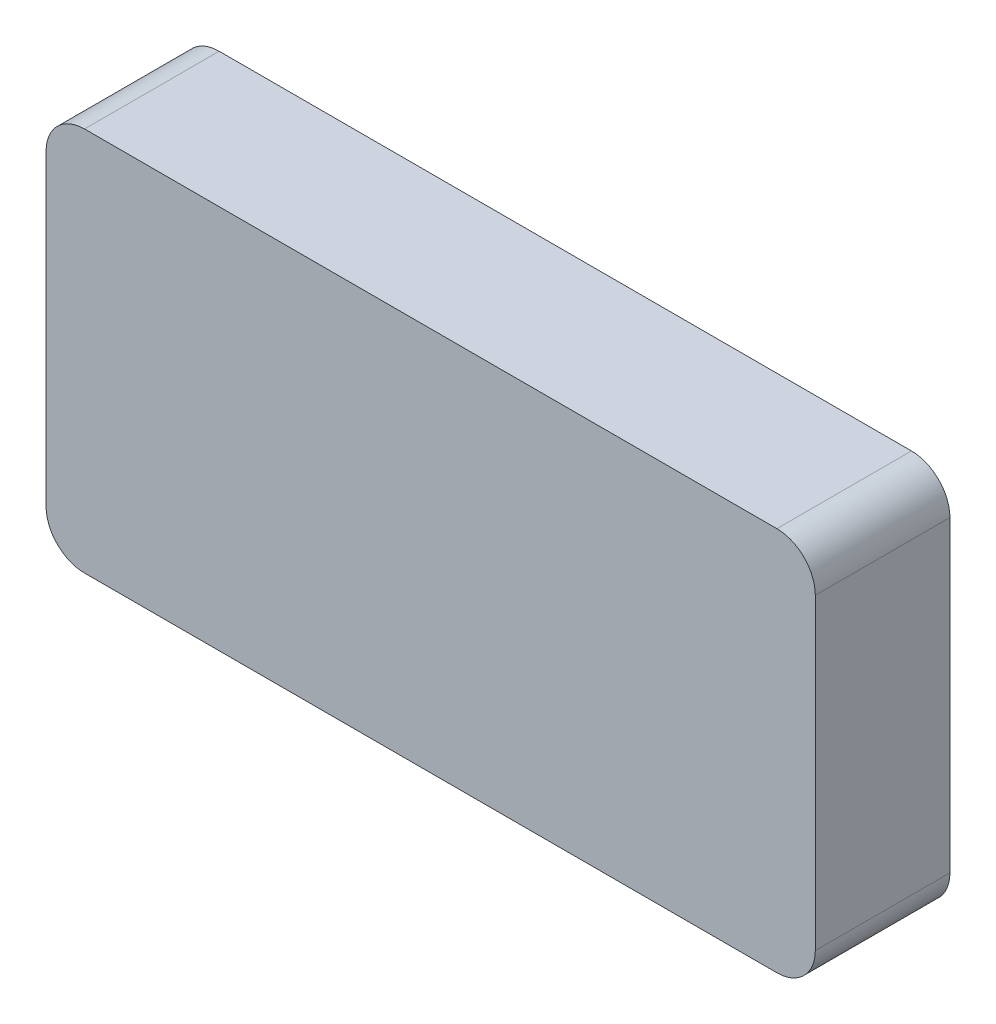
SolidWorks part; units mm, degrees
ref_plane "Front Plane" through (0, 0, 0) normal (0, 0, 1) x (1, 0, 0)
ref_plane "Top Plane" through (0, 0, 0) normal (0, 1, 0) x (1, 0, 0)
ref_plane "Right Plane" through (0, 0, 0) normal (1, 0, 0) x (0, 0, -1)
sketch "Sketch1" plane through (0, 0, 0) normal (0, 0, 1) x (1, 0, 0)
  line L0 (-10, 0) -> (0, 0) construction
  line L1 (-9, 5) -> (9, 5)
  line L2 (-10, 4) -> (-10, -4)
  line L3 (-9, -5) -> (9, -5)
  line L4 (10, 4) -> (10, -4)
  line L5 (0, 0) -> (0, 5) construction
  arc A0 (9, 5) -> (10, 4) centre (9, 4) cw
  arc A1 (-10, -4) -> (-9, -5) centre (-9, -4) ccw
  arc A2 (9, -5) -> (10, -4) centre (9, -4) ccw
  arc A3 (-9, 5) -> (-10, 4) centre (-9, 4) ccw
  point P11 (10, 5)
  point P16 (10, -5)
  point P19 (-10, 5)
  dimension "D3" = 1
  dimension "D1" = 20
  dimension "D2" = 10
extrude "Boss-Extrude1" add sketch "Sketch1" along normal blind 3.5
sketch "Sketch2" plane through (0, 0, 0) normal (0, 0, -1) x (-1, 0, 0)
  line L0 (-9, 0) -> (0, 0) construction
  line L1 (-9, 4) -> (9, 4)
  line L2 (-9, 4) -> (-9, -4)
  line L3 (-9, -4) -> (9, -4)
  line L4 (9, 4) -> (9, -4)
  line L5 (0, 0) -> (0, 4) construction
  dimension "D1" = 18
  dimension "D2" = 8
extrude "Cut-Extrude1" cut sketch "Sketch2" against normal blind 1
